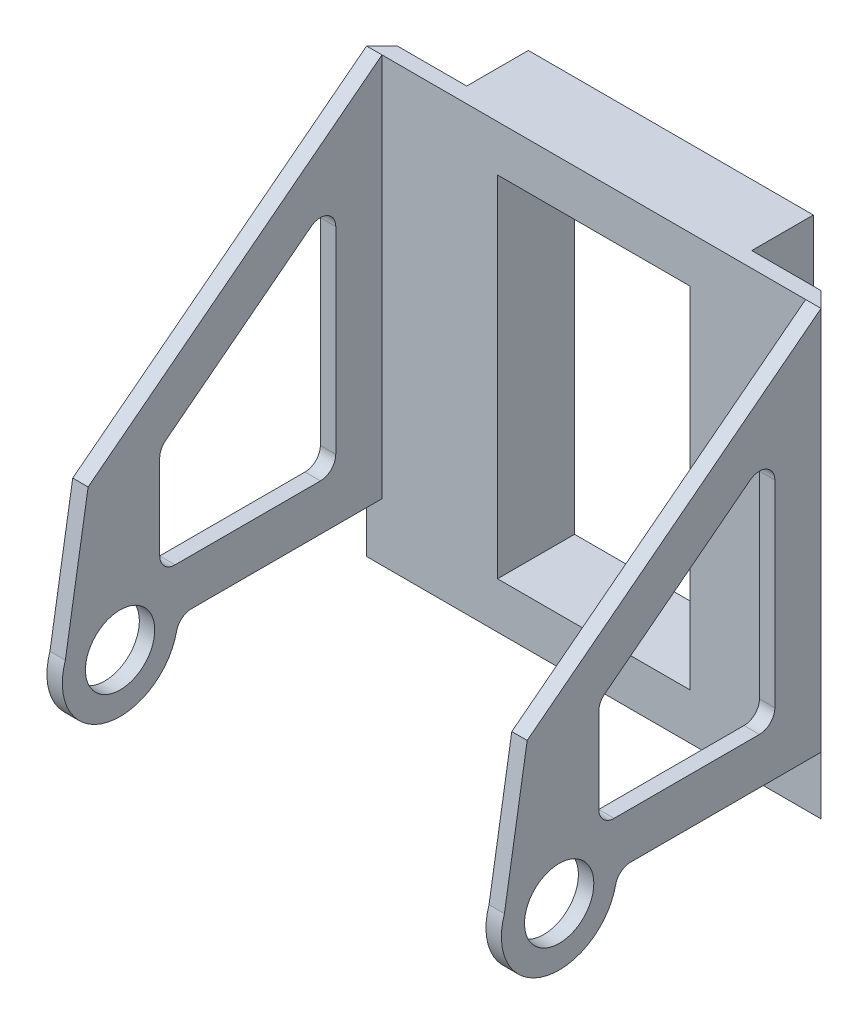
SolidWorks part; units mm, degrees
ref_plane "前视基准面" through (0, 0, 0) normal (0, 0, 1) x (1, 0, 0)
ref_plane "上视基准面" through (0, 0, 0) normal (0, 1, 0) x (1, 0, 0)
ref_plane "右视基准面" through (0, 0, 0) normal (1, 0, 0) x (0, 0, -1)
other "Configuration Table"
sketch "草图1" plane through (0, 0, 0) normal (0, 0, 1) x (1, 0, 0)
  line L0 (-3, -3) -> (-3, 25.7)
  line L1 (0, 0) -> (12.5, 0)
  line L2 (0, 0) -> (0, 22.7)
  line L3 (0, 22.7) -> (12.5, 22.7)
  line L4 (12.5, 0) -> (12.5, 22.7)
  line L5 (-3, 25.7) -> (15.5, 25.7)
  line L6 (15.5, -3) -> (15.5, 25.7)
  line L7 (-3, -3) -> (15.5, -3)
  dimension "D1" = 12.5
  dimension "D2" = 22.7
  dimension "D3" = 3
extrude "凸台-拉伸1" add sketch "草图1" along normal blind 5
sketch "草图2" plane through (0, -3, 0) normal (0, -1, 0) x (1, 0, 0)
  line L0 (6.25, 5) -> (6.25, 0) construction
  line L1 (-3, 5) -> (15.5, 5) construction
  line L2 (-3, 0) -> (15.5, 0) construction
  line L3 (-3, 5) -> (-3, 4)
  line L4 (-3, 5) -> (-3, 0) construction
  line L5 (-3, 4) -> (-8.5, 4)
  line L6 (-8.5, 4) -> (-8.5, 26)
  line L7 (-8.5, 26) -> (-7.5, 26)
  line L8 (-7.5, 26) -> (-7.5, 5)
  line L9 (-7.5, 5) -> (-3, 5)
  line L10 (20, 26) -> (20, 5)
  line L11 (21, 26) -> (20, 26)
  line L12 (21, 4) -> (21, 26)
  line L13 (15.5, 4) -> (21, 4)
  line L14 (15.5, 5) -> (15.5, 4)
  line L15 (20, 5) -> (15.5, 5)
  dimension "D1" = 1
  dimension "D2" = 1
  dimension "D3" = 5.5
  dimension "D4" = 22
extrude "凸台-拉伸2" add sketch "草图2" against normal up to surface (28.7 mm away) up to face at (6.25, 25.7, 2.5)
chamfer "倒角1" distance 1 angle 45 2 edges at (21, 11.35, 4) (-8.5, 11.35, 4)
sketch "草图3" plane through (21, 0, 0) normal (1, 0, 0) x (0, 0, -1)
  line L1 (-26, 25.7) -> (-26, -3) construction
  line L2 (-18.25, -3) -> (-18.25, 0.75)
  line L3 (-25.75, 0.75) -> (-24.0747, 10.9495)
  line L4 (-5, -3) -> (-26, -3) construction
  line L5 (-18.25, 0.75) -> (-5, 0.75)
  line L6 (-5, -3) -> (-5, 25.7) construction
  line L7 (-24.0747, 10.9495) -> (-5, 25.7)
  line L8 (-25.75, 0.75) -> (-26, 0.75)
  line L9 (-26, 0.75) -> (-26, 25.7)
  line L10 (-26, 25.7) -> (-5, 25.7)
  line L11 (-26, 0.75) -> (-26, -3)
  line L12 (-26, -3) -> (-22, -3)
  line L13 (-18.25, -3) -> (-22, -3)
  circle A0 centre (-22, 0.75) radius 3.75
  line M5 (-26, -3) -> (-5, -3)
  line M6 (-5, -3) -> (-5, 25.7)
  line M7 (-5, 25.7) -> (-26, 25.7)
  line M8 (-26, 25.7) -> (-26, -3)
  dimension "D1" = 7.5
  dimension "D2" = 4
extrude "切除-拉伸1" cut sketch "草图3" against normal through all contours A0 L3 L7 L8 M7 M8 | A0 L8 M8 M5 | A0 L2 M5 | L5 L2 M5 M6
fillet "圆角1" radius 1 2 edges at (-8, 0.75, 18.25) (20.5, 0.75, 18.25)
sketch "草图5" plane through (21, 0, 0) normal (1, 0, 0) x (0, 0, -1)
  line L0 (-19.4285, 3.75) -> (-19.4285, 10.75)
  line L1 (-19.4285, 10.75) -> (-8, 19.5877)
  line L2 (-8, 19.5877) -> (-8, 3.75)
  line L3 (-8, 3.75) -> (-19.4285, 3.75)
  line L4 (-17.3565, 0.75) -> (-5, 0.75) construction
  line L6 (-24.0747, 10.9495) -> (-5, 25.7) construction
  line L7 (-5, 0.75) -> (-5, 25.7) construction
  point P10 (0, 0)
  dimension "D1" = 3
  dimension "D2" = 3
  dimension "D3" = 3
  dimension "D4" = 7
extrude "切除-拉伸2" cut sketch "草图5" against normal through all
fillet "圆角2" radius 1 8 edges at (-8, 3.75, 19.4285) (-8, 19.5877, 8) (-8, 3.75, 8) (-8, 10.75, 19.4285) (20.5, 3.75, 19.4285) (20.5, 19.5877, 8) (20.5, 3.75, 8) (20.5, 10.75, 19.4285)
sketch "草图6" plane through (21, 0, 0) normal (1, 0, 0) x (0, 0, -1)
  line L4 (-17.3565, 0.75) -> (-5, 0.75)
  line L5 (-5, 0.75) -> (-5, 25.7)
  line L6 (-5, 25.7) -> (-24.0747, 10.9495)
  line L7 (-24.0747, 10.9495) -> (-25.553, 1.9495)
  line L8 (-17.3565, 0.75) -> (-5, 0.75)
  line L9 (-5, 0.75) -> (-5, 25.7)
  line L10 (-5, 25.7) -> (-24.0747, 10.9495)
  line L11 (-24.0747, 10.9495) -> (-25.553, 1.9495)
  circle A0 centre (-22, 0.75) radius 2.25
  arc A2 (-25.553, 1.9495) -> (-18.334, -0.0395) centre (-22, 0.75) ccw
  arc A3 (-17.3565, 0.75) -> (-18.334, -0.0395) centre (-17.3565, -0.25) ccw
  arc A4 (-25.553, 1.9495) -> (-18.334, -0.0395) centre (-22, 0.75) ccw
  arc A5 (-17.3565, 0.75) -> (-18.334, -0.0395) centre (-17.3565, -0.25) ccw
  dimension "D2" = 4.5
  dimension "D1" = 0
extrude "切除-拉伸3" cut sketch "草图6" against normal through all contours A0
